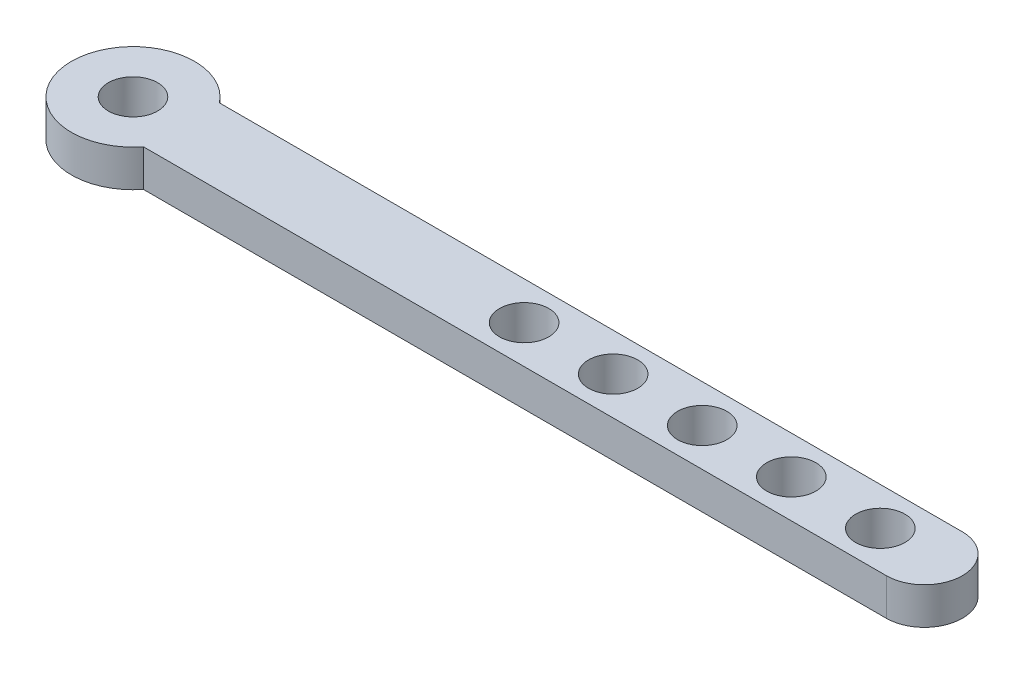
SolidWorks part; units mm, degrees
ref_plane "Front Plane" through (0, 0, 0) normal (0, 0, 1) x (1, 0, 0)
ref_plane "Top Plane" through (0, 0, 0) normal (0, 1, 0) x (1, 0, 0)
ref_plane "Right Plane" through (0, 0, 0) normal (1, 0, 0) x (0, 0, -1)
sketch "Sketch2" plane through (0, 0, 0) normal (0, 1, 0) x (1, 0, 0)
  line L1 (-32.1334, 3.0866) -> (32.1334, 3.0866)
  line L2 (-32.1334, 3.0866) -> (-32.1334, -3.0866)
  line L3 (-32.1334, -3.0866) -> (32.1334, -3.0866)
  line L5 (-32.1334, 3.0866) -> (32.1334, -3.0866) construction
  line L6 (-32.1334, -3.0866) -> (32.1334, 3.0866) construction
  arc A1 (32.1334, 3.0866) -> (32.1334, -3.0866) centre (32.1334, 0) cw
  circle A2 centre (28.5588, 0) radius 2
  circle A3 centre (21.3267, 0) radius 2
  circle A4 centre (14.0946, 0) radius 2
  circle A5 centre (6.8625, 0) radius 2
  circle A6 centre (-0.3696, 0) radius 2
  point P0 (0, 0)
  dimension "D2" = 4
  dimension "D1" = 5
extrude "Boss-Extrude2" add sketch "Sketch2" along normal blind 3
sketch "Sketch6" plane through (0, 3, 0) normal (0, 1, 0) x (1, 0, 0)
  line L0 (-32.1334, 3.0866) -> (-32.1334, -3.0866) construction
  circle A0 centre (-32.1334, 0) radius 5
  dimension "D1" = 10
extrude "Boss-Extrude5" add sketch "Sketch6" against normal up to surface (3 mm away) up to face at (6.8625, 0, 2)
sketch "Sketch8" plane through (0, 3, 0) normal (0, 1, 0) x (1, 0, 0)
  circle A0 centre (-32.1334, 0) radius 2
  dimension "D1" = 4
extrude "Cut-Extrude3" cut sketch "Sketch8" against normal blind 10
